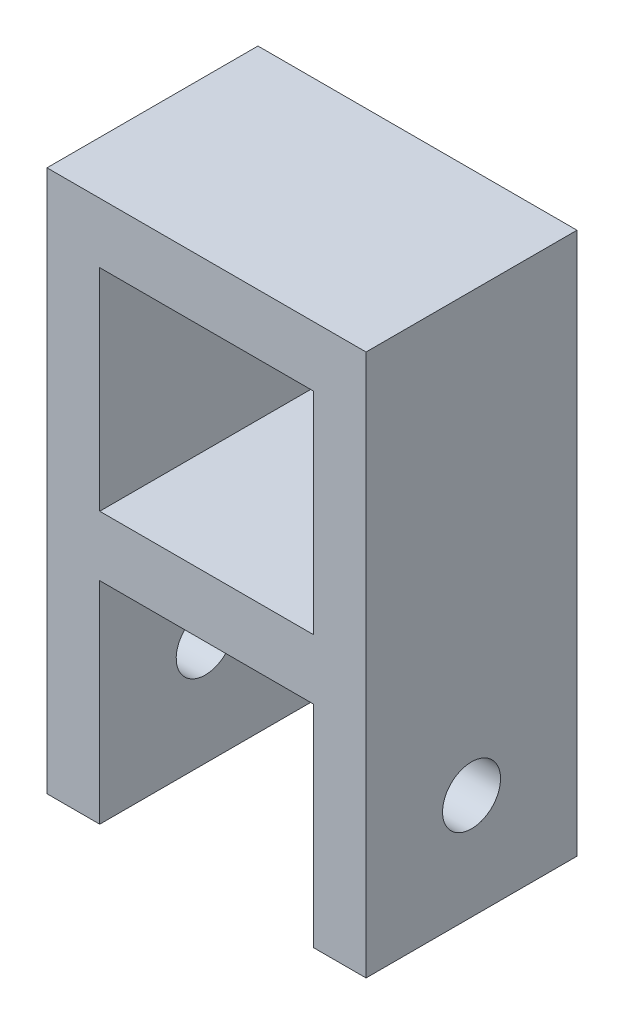
SolidWorks part; units mm, degrees
ref_plane "Front Plane" through (0, 0, 0) normal (0, 0, 1) x (1, 0, 0)
ref_plane "Top Plane" through (0, 0, 0) normal (0, 1, 0) x (1, 0, 0)
ref_plane "Right Plane" through (0, 0, 0) normal (1, 0, 0) x (0, 0, -1)
sketch "Sketch1" plane through (0, 0, 0) normal (0, 0, 1) x (1, 0, 0)
  line L0 (0, 60.4) -> (0, -56.6) construction
  line L1 (-78.4, 0) -> (59.8, 0) construction
  line L2 (-10.125, 0) -> (-10.125, 20)
  line L3 (-10.125, 20) -> (10.125, 20)
  line L4 (-10.125, 0) -> (-15.125, 0)
  line L5 (-15.125, 0) -> (-15.125, 51.4)
  line L6 (-15.125, 51.4) -> (15.125, 51.4)
  line L7 (15.125, 0) -> (15.125, 51.4)
  line L8 (10.125, 0) -> (15.125, 0)
  line L9 (10.125, 0) -> (10.125, 20)
  line L11 (-10.125, 45.7) -> (10.125, 45.7)
  line L12 (-10.125, 45.7) -> (-10.125, 25.7)
  line L13 (-10.125, 25.7) -> (10.125, 25.7)
  line L14 (10.125, 45.7) -> (10.125, 25.7)
  point P12 (0, 51.4)
  point P15 (0, 20)
  dimension "D1" = 20
  dimension "D2" = 10.125
  dimension "D3" = 5
  dimension "D4" = 31.4
  dimension "D5" = 20
  dimension "D6" = 5.7
extrude "Boss-Extrude1" add sketch "Sketch1" along normal blind 20
sketch "Sketch2" plane through (0, 0, 0) normal (1, 0, 0) x (0, 0, -1)
  circle A0 centre (-10, 10) radius 2.75
  dimension "D1" = 5.5
  dimension "D2" = 10
  dimension "D3" = 10
extrude "Cut-Extrude1" cut sketch "Sketch2" against normal through all both and the other way through all
